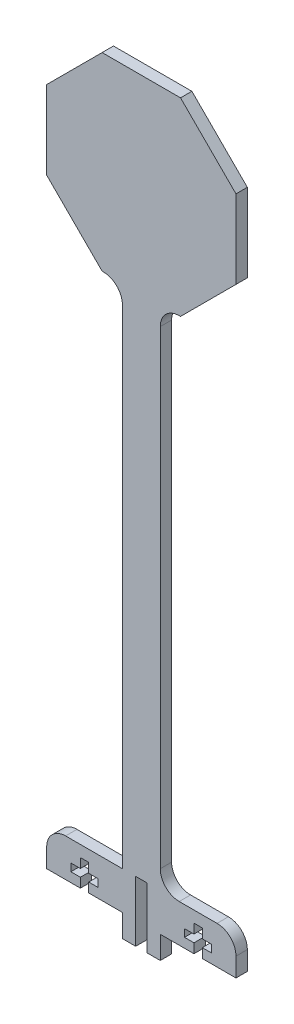
SolidWorks part; units mm, degrees
ref_plane "Front Plane" through (0, 0, 0) normal (0, 0, 1) x (1, 0, 0)
ref_plane "Top Plane" through (0, 0, 0) normal (0, 1, 0) x (1, 0, 0)
ref_plane "Right Plane" through (0, 0, 0) normal (1, 0, 0) x (0, 0, -1)
sketch "Sketch1" plane through (0, 0, 0) normal (0, 0, 1) x (1, 0, 0)
  line L0 (-5, -25) -> (-5, -159)
  line L7 (-5, -175) -> (-1.5, -175)
  line L8 (5, -175) -> (5, -169)
  line L10 (-5, -169) -> (-13.9, -169)
  line L11 (-25, -169) -> (-25, -159)
  line L12 (-25, -159) -> (-5, -159)
  line L13 (-16.1, -169) -> (-16.1, -166.5)
  line L14 (0, 25) -> (0, -175) construction
  line L15 (-16.1, -166.5) -> (-18.6, -166.5)
  line L16 (-18.6, -166.5) -> (-18.6, -164.5)
  line L17 (-18.6, -164.5) -> (-16.1, -164.5)
  line L18 (-16.1, -164.5) -> (-16.1, -162)
  line L19 (-16.1, -162) -> (-13.9, -162)
  line L20 (-13.9, -162) -> (-13.9, -164.5)
  line L21 (-13.9, -164.5) -> (-11.4, -164.5)
  line L22 (-11.4, -164.5) -> (-11.4, -166.5)
  line L23 (-11.4, -166.5) -> (-13.9, -166.5)
  line L24 (-13.9, -166.5) -> (-13.9, -169)
  line L25 (-15, -159) -> (-15, -169) construction
  line L26 (15, -159) -> (15, -169) construction
  line L27 (13.9, -166.5) -> (13.9, -169)
  line L28 (11.4, -166.5) -> (13.9, -166.5)
  line L29 (11.4, -164.5) -> (11.4, -166.5)
  line L30 (13.9, -164.5) -> (11.4, -164.5)
  line L31 (13.9, -162) -> (13.9, -164.5)
  line L32 (16.1, -162) -> (13.9, -162)
  line L33 (16.1, -164.5) -> (16.1, -162)
  line L34 (18.6, -164.5) -> (16.1, -164.5)
  line L35 (18.6, -166.5) -> (18.6, -164.5)
  line L36 (16.1, -166.5) -> (18.6, -166.5)
  line L37 (16.1, -169) -> (16.1, -166.5)
  line L38 (25, -159) -> (5, -159)
  line L39 (25, -169) -> (25, -159)
  line L40 (5, -169) -> (13.9, -169)
  line L41 (-16.1, -169) -> (-25, -169)
  line L42 (16.1, -169) -> (25, -169)
  line L43 (5, -159) -> (5, -25)
  line L44 (-5, -169) -> (-5, -175)
  line L45 (-1.5, -175) -> (-1.5, -159)
  line L46 (-1.5, -159) -> (1.5, -159)
  line L47 (1.5, -159) -> (1.5, -175)
  line L48 (1.5, -175) -> (5, -175)
  line L60 (5, -25) -> (10.3553, -25)
  line L61 (25, 10.3553) -> (10.3553, 25)
  line L62 (10.3553, 25) -> (-10.3553, 25)
  line L63 (-10.3553, 25) -> (-25, 10.3553)
  line L64 (-25, 10.3553) -> (-25, -10.3553)
  line L65 (-25, -10.3553) -> (-10.3553, -25)
  line L66 (-10.3553, -25) -> (-5, -25)
  line L67 (10.3553, -25) -> (25, -10.3553)
  line L68 (25, -10.3553) -> (25, 10.3553)
  circle A0 centre (0, 0) radius 25 construction
  point P0 (0, 0)
  point P36 (-15, -162)
  point P57 (0, -159)
  dimension "D3" = 200
  dimension "D6" = 50
  dimension "D2" = 25
  dimension "D4" = 25
  dimension "D5" = 5
  dimension "D7" = 25
  dimension "D8" = 150
  dimension "D9" = 10
  dimension "D10" = 20
  dimension "D11" = 6
  dimension "D12" = 2.5
  dimension "D13" = 2
  dimension "D14" = 2.5
  dimension "D15" = 2.5
  dimension "D16" = 2.2
  dimension "D17" = 2.5
  dimension "D18" = 16
  dimension "D19" = 1.5
extrude "Boss-Extrude1" add sketch "Sketch1" along normal blind 3
fillet "Fillet1" radius 5 5 edges at (5, -159, 1.5) (25, -159, 1.5) (-25, -159, 1.5) (5, -25, 1.5) (-5, -25, 1.5)
